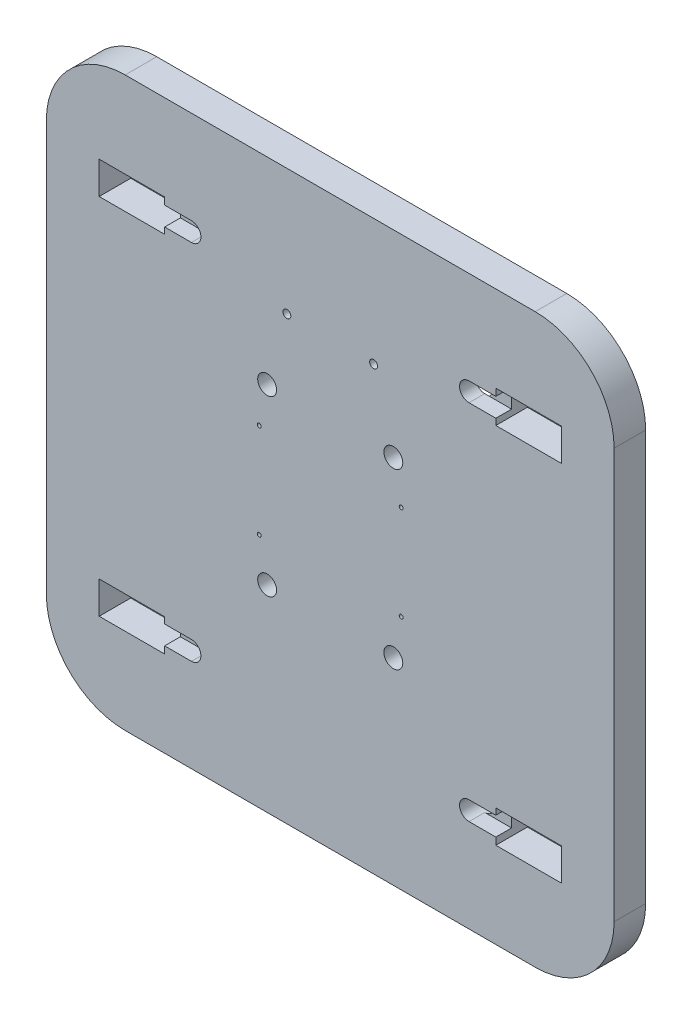
SolidWorks part; units mm, degrees
ref_plane "Front Plane" through (0, 0, 0) normal (0, 0, 1) x (1, 0, 0)
ref_plane "Top Plane" through (0, 0, 0) normal (0, 1, 0) x (1, 0, 0)
ref_plane "Right Plane" through (0, 0, 0) normal (1, 0, 0) x (0, 0, -1)
sketch "Sketch1" plane through (0, 0, 0) normal (0, 0, 1) x (1, 0, 0)
  line L1 (50, 360) -> (310, 360)
  line L2 (0, 310) -> (0, 50)
  line L3 (50, 0) -> (310, 0)
  line L4 (360, 310) -> (360, 50)
  arc A0 (0, 310) -> (50, 360) centre (50, 310) cw
  arc A1 (310, 360) -> (360, 310) centre (310, 310) cw
  arc A2 (310, 0) -> (360, 50) centre (310, 50) ccw
  arc A3 (50, 0) -> (0, 50) centre (50, 50) cw
  point P8 (0, 360)
  point P11 (360, 360)
  point P14 (360, 0)
  point P17 (0, 0)
  dimension "D3" = 50
  dimension "D1" = 360
  dimension "D2" = 360
extrude "Boss-Extrude1" add sketch "Sketch1" along normal mid plane 20
sketch "Sketch2" plane through (0, 0, 10) normal (0, 0, 1) x (1, 0, 0)
  line L1 (33.5, 305.5) -> (75, 305.5)
  line L2 (33.5, 305.5) -> (33.5, 285)
  line L3 (33.5, 285) -> (75, 285)
  line L4 (75, 305.5) -> (75, 285)
  line L5 (285, 305.5) -> (326.5, 305.5)
  line L6 (285, 305.5) -> (285, 285)
  line L7 (285, 285) -> (326.5, 285)
  line L8 (326.5, 305.5) -> (326.5, 285)
  line L9 (285, 75) -> (326.5, 75)
  line L10 (285, 75) -> (285, 54.5)
  line L11 (285, 54.5) -> (326.5, 54.5)
  line L12 (326.5, 75) -> (326.5, 54.5)
  line L13 (33.5, 75) -> (75, 75)
  line L14 (33.5, 75) -> (33.5, 54.5)
  line L15 (33.5, 54.5) -> (75, 54.5)
  line L16 (75, 75) -> (75, 54.5)
  point P16 (305.75, 285)
  point P19 (180, 180)
  dimension "D1" = 41.5
  dimension "D2" = 20.5
  dimension "D3" = 20.5
  dimension "D4" = 41.5
  dimension "D5" = 41.5
  dimension "D6" = 20.5
  dimension "D7" = 20.5
  dimension "D8" = 41.5
  dimension "D9" = 210
  dimension "D10" = 210
  dimension "D11" = 180
  dimension "D12" = 180
  dimension "D13" = 105
  dimension "D14" = 105
extrude "Cut-Extrude1" cut sketch "Sketch2" against normal blind 20
sketch "Sketch3" plane through (0, 0, 10) normal (0, 0, 1) x (1, 0, 0)
  line L0 (75, 285) -> (75, 305.5) construction
  line L1 (285, 305.5) -> (285, 285) construction
  line L2 (33.5, 285) -> (75, 285) construction
  line L3 (75, 75) -> (33.5, 75) construction
  circle A0 centre (92, 295) radius 6
  circle A1 centre (268, 295) radius 6
  circle A2 centre (268, 65) radius 6
  circle A3 centre (92, 65) radius 6
  point P17 (285, 295.25)
  dimension "D1" = 12
  dimension "D2" = 17
  dimension "D3" = 17
  dimension "D4" = 10
  dimension "D5" = 10
extrude "Cut-Extrude2" cut sketch "Sketch3" against normal through all
sketch "Sketch4" plane through (0, 0, 10) normal (0, 0, 1) x (1, 0, 0)
  line L0 (0, 310) -> (0, 50) construction
  line L1 (50, 0) -> (310, 0) construction
  circle A0 centre (140, 235) radius 6
  circle A1 centre (220, 235) radius 6
  circle A2 centre (220, 125) radius 6
  circle A3 centre (140, 125) radius 6
  point P12 (180, 180)
  dimension "D1" = 110
  dimension "2" = 12
  dimension "D2" = 80
  dimension "D3" = 180
  dimension "D4" = 180
  dimension "D5" = 40
  dimension "D6" = 55
extrude "Cut-Extrude3" cut sketch "Sketch4" against normal through all
sketch "Sketch10" plane through (0, 0, -10) normal (0, 0, -1) x (-1, 0, 0)
  line L0 (-92, 295) -> (-140, 235) construction
  line L1 (-87.3148, 291.2518) -> (-135.3148, 231.2518)
  line L2 (-96.6852, 298.7482) -> (-144.6852, 238.7482)
  line L3 (-96.6852, 298.7482) -> (-87.3148, 291.2518)
  line L4 (-135.3148, 231.2518) -> (-144.6852, 238.7482)
  line L5 (-268, 295) -> (-220, 235) construction
  line L6 (-268, 65) -> (-220, 125) construction
  line L7 (-92, 65) -> (-140, 125) construction
  line L8 (-263.3148, 61.2518) -> (-215.3148, 121.2518)
  line L9 (-87.3148, 68.7482) -> (-135.3148, 128.7482)
  line L10 (-272.6852, 291.2518) -> (-224.6852, 231.2518)
  line L11 (-272.6852, 68.7482) -> (-224.6852, 128.7482)
  line L12 (-96.6852, 61.2518) -> (-144.6852, 121.2518)
  line L13 (-263.3148, 298.7482) -> (-215.3148, 238.7482)
  line L14 (-87.3148, 68.7482) -> (-96.6852, 61.2518)
  line L15 (-135.3148, 128.7482) -> (-144.6852, 121.2518)
  line L16 (-224.6852, 128.7482) -> (-215.3148, 121.2518)
  line L17 (-263.3148, 61.2518) -> (-272.6852, 68.7482)
  line L18 (-215.3148, 238.7482) -> (-224.6852, 231.2518)
  line L19 (-263.3148, 298.7482) -> (-272.6852, 291.2518)
  dimension "D1" = 6
  dimension "D2" = 6
  dimension "D3" = 6
  dimension "D4" = 6
extrude "Cut-Extrude4" cut sketch "Sketch10" against normal blind 10
sketch "Sketch11" plane through (0, 0, 10) normal (0, 0, 1) x (1, 0, 0)
  line L0 (92, 65) -> (71.6456, 65) construction
  line L1 (268, 65) -> (292.3509, 65) construction
  line L2 (268, 295) -> (292.3509, 295) construction
  line L3 (92, 295) -> (62.0027, 295) construction
  line L4 (92, 71) -> (71.6456, 71)
  line L5 (268, 59) -> (292.3509, 59)
  line L6 (268, 289) -> (292.3509, 289)
  line L7 (92, 301) -> (62.0027, 301)
  line L8 (92, 59) -> (71.6456, 59)
  line L9 (268, 71) -> (292.3509, 71)
  line L10 (268, 301) -> (292.3509, 301)
  line L11 (92, 289) -> (62.0027, 289)
  line L12 (92, 301) -> (92, 289)
  line L13 (62.0027, 301) -> (62.0027, 289)
  line L14 (268, 301) -> (268, 289)
  line L15 (292.3509, 289) -> (292.3509, 301)
  line L16 (292.3509, 71) -> (292.3509, 59)
  line L17 (268, 59) -> (268, 71)
  line L18 (92, 71) -> (92, 59)
  line L19 (71.6456, 71) -> (71.6456, 59)
  dimension "D1" = 6
  dimension "D2" = 6
extrude "Cut-Extrude5" cut sketch "Sketch11" against normal blind 10 contours L4 L19 L8 L18 | L5 L16 L9 L17 | L10 L15 L6 L14 | L11 L13 L7 L12
sketch "Sketch12" plane through (0, 0, 10) normal (0, 0, 1) x (1, 0, 0)
  line L0 (0, 310) -> (0, 50) construction
  line L1 (50, 0) -> (310, 0) construction
  point P0 (180, 180)
  dimension "D1" = 180
  dimension "D2" = 180
hole_wizard "M3 Tapped Hole1" positions "3DSketch1" profile "Sketch13" tap size "M3" standard "ISO" end condition through all
sketch3d "3DSketch1"
  line L0 (0, 310, 10) -> (0, 50, 10) construction
  line L1 (50, 0, 10) -> (310, 0, 10) construction
  point P0 (135, 150, 10)
  point P2 (225, 210, 10)
  point P4 (135, 210, 10)
  point P5 (225, 150, 10)
  dimension "D1" = 135
  dimension "D2" = 225
  dimension "D3" = 150
  dimension "D4" = 210
cosmetic thread "Hole Thread1" parameters "D2"=3
cosmetic thread "Hole Thread2" parameters "D2"=3
cosmetic thread "Hole Thread3" parameters "D2"=3
cosmetic thread "Hole Thread4" parameters "D2"=3
sketch "Sketch13" plane through (135, 150, 10) normal (1, 0, 0) x (0, -1, 0)
  line L0 (0, 0) -> (0, 20)
  line L1 (0, 20) -> (1.25, 20)
  line L2 (1.25, 20) -> (1.25, 0)
  line L5 (1.25, 0) -> (0, 0)
  line L11 (0, -6.35) -> (0, 107.95) construction
  dimension "Thru Tap Drill Dia." = 2.5
  dimension "Thru Tap Drill Depth" = 20
hole_wizard "M6 Tapped Hole1" positions "3DSketch2" profile "Sketch15" tap size "M6" standard "ISO" end condition through all
sketch3d "3DSketch2"
  line L0 (310, 360, 10) -> (50, 360, 10) construction
  line L1 (0, 310, 10) -> (0, 50, 10) construction
  point P0 (152.5, 280, 10)
  point P2 (207.5, 280, 10)
  dimension "D1" = 80
  dimension "D2" = 55
  dimension "D3" = 152.5
sketch "Sketch15" plane through (152.5, 280, 10) normal (1, 0, 0) x (0, -1, 0)
  line L0 (0, 0) -> (0, 20)
  line L1 (0, 20) -> (2.5, 20)
  line L2 (2.5, 20) -> (2.5, 0)
  line L5 (2.5, 0) -> (0, 0)
  line L11 (0, -6.35) -> (0, 107.95) construction
  dimension "Thru Tap Drill Dia." = 5
  dimension "Thru Tap Drill Depth" = 20
cosmetic thread "Hole Thread5" parameters "D2"=6
cosmetic thread "Hole Thread6" parameters "D2"=6
